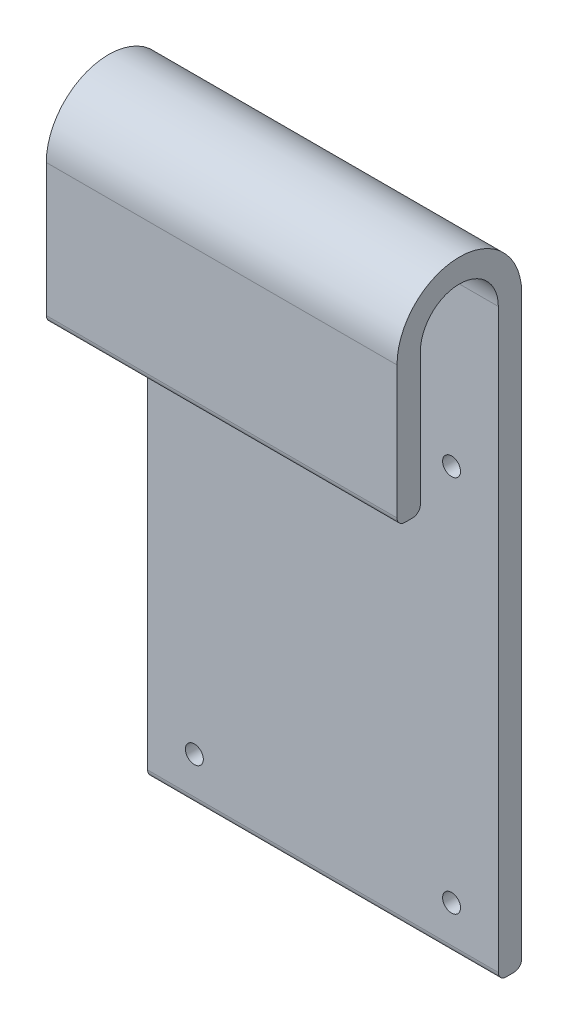
SolidWorks part; units mm, degrees
ref_plane "Front Plane" through (0, 0, 0) normal (0, 0, 1) x (1, 0, 0)
ref_plane "Top Plane" through (0, 0, 0) normal (0, 1, 0) x (1, 0, 0)
ref_plane "Right Plane" through (0, 0, 0) normal (1, 0, 0) x (0, 0, -1)
sketch "Sketch1" plane through (0, 0, 0) normal (1, 0, 0) x (0, 0, -1)
  line L0 (0, 0) -> (0, 75)
  line L1 (-10, 75) -> (-10, 57)
  arc A0 (0, 75) -> (-10, 75) centre (-5, 75) ccw
  point P5 (-5, 80)
  dimension "D1" = 5
  dimension "D2" = 80
  dimension "D3" = 18
extrude "Extrude-Thin1" add sketch "Sketch1" along normal mid plane 45 thin
sketch "Sketch2" plane through (0, 0, -3) normal (0, 0, -1) x (-1, 0, 0)
  circle A1 centre (-16.5, 54.2458) radius 1.15
  circle A2 centre (-16.5, 54.2458) radius 1.15
  circle A3 centre (16.5, 54.2458) radius 1.15
  circle A4 centre (16.5, 54.2458) radius 1.15
  circle A5 centre (16.5, 5.7458) radius 1.15
  circle A6 centre (16.5, 5.7458) radius 1.15
  circle A7 centre (-16.5, 5.7458) radius 1.15
  circle A8 centre (-16.5, 5.7458) radius 1.15
  dimension "D1" = 0
  dimension "D2" = 0
  dimension "D3" = 0
  dimension "D4" = 0
extrude "Cut-Extrude1" cut sketch "Sketch2" against normal through all
fillet "Fillet1" radius 1 4 edges at (0, 57, 10) (0, 57, 13) (0, 0, -3) (0, 0, 0)
